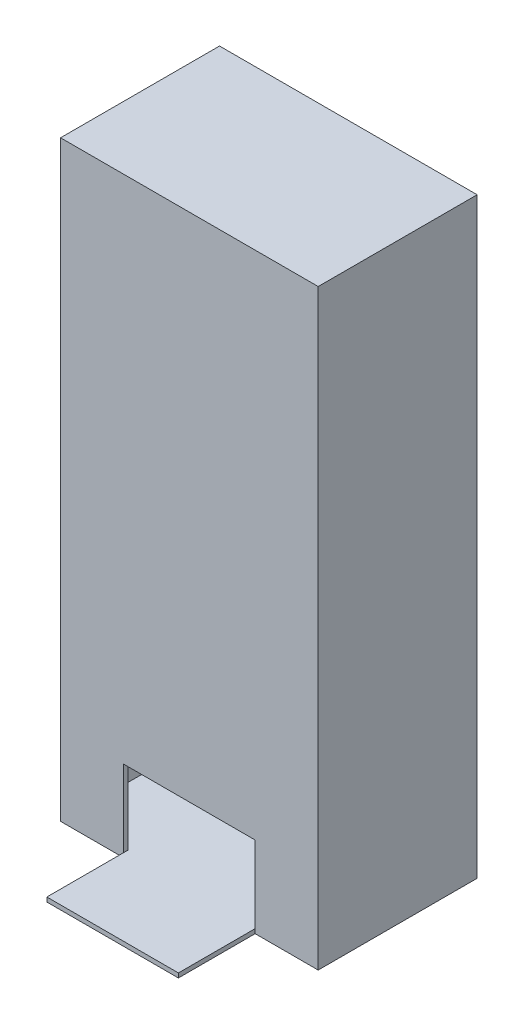
SolidWorks part; units mm, degrees
ref_plane "Plan de face" through (0, 0, 0) normal (0, 0, 1) x (1, 0, 0)
ref_plane "Plan de dessus" through (0, 0, 0) normal (0, 1, 0) x (1, 0, 0)
ref_plane "Plan de droite" through (0, 0, 0) normal (1, 0, 0) x (0, 0, -1)
sketch "Esquisse1" plane through (0, 0, 0) normal (0, 0, 1) x (1, 0, 0)
  line L1 (0, 0) -> (235, 0)
  line L2 (0, 0) -> (0, -540)
  line L3 (0, -540) -> (235, -540)
  line L4 (235, 0) -> (235, -540)
  dimension "D1" = 235
  dimension "D2" = 540
extrude "Boss.-Extru.1" add sketch "Esquisse1" along normal blind 145
sketch "Esquisse2" plane through (0, 0, 145) normal (0, 0, 1) x (1, 0, 0)
  line L0 (235, 0) -> (0, 0) construction
  line L1 (4, -4) -> (231, -4)
  line L2 (4, -4) -> (4, -536)
  line L3 (4, -536) -> (231, -536)
  line L4 (231, -4) -> (231, -536)
  line L5 (235, -540) -> (235, 0) construction
  line L6 (0, -540) -> (235, -540) construction
  line L7 (0, 0) -> (0, -540) construction
  dimension "D1" = 4
  dimension "D2" = 4
  dimension "D3" = 4
  dimension "D4" = 4
extrude "Enlèv. mat.-Extru.1" cut sketch "Esquisse2" against normal blind 141
sketch "Esquisse3" plane through (0, 0, 145) normal (0, 0, 1) x (1, 0, 0)
  line L1 (0, 0) -> (235, 0)
  line L2 (0, 0) -> (0, -540)
  line L3 (0, -540) -> (235, -540)
  line L4 (235, 0) -> (235, -540)
extrude "Boss.-Extru.2" add sketch "Esquisse3" against normal blind 4
sketch "Esquisse4" plane through (0, 0, 145) normal (0, 0, 1) x (1, 0, 0)
  line L0 (0, -540) -> (235, -540) construction
  line L1 (57.5, -466) -> (177.5, -466)
  line L2 (57.5, -466) -> (57.5, -536)
  line L3 (57.5, -536) -> (177.5, -536)
  line L4 (177.5, -466) -> (177.5, -536)
  line L5 (117.5, -536) -> (117.5, -510.201) construction
  line L6 (117.5, -540) -> (117.5, -521.8521)
  dimension "D1" = 120
  dimension "D2" = 70
  dimension "D3" = 4
extrude "Enlèv. mat.-Extru.2" cut sketch "Esquisse4" against normal blind 4
sketch "Esquisse5" plane through (0, 0, 145) normal (0, 0, 1) x (1, 0, 0)
  line L0 (0, -540) -> (235, -540) construction
  line L1 (57.5, -536) -> (177.5, -536)
  line L2 (57.5, -536) -> (57.5, -540)
  line L3 (57.5, -540) -> (177.5, -540)
  line L4 (177.5, -536) -> (177.5, -540)
extrude "Boss.-Extru.3" add sketch "Esquisse5" along normal blind 70
